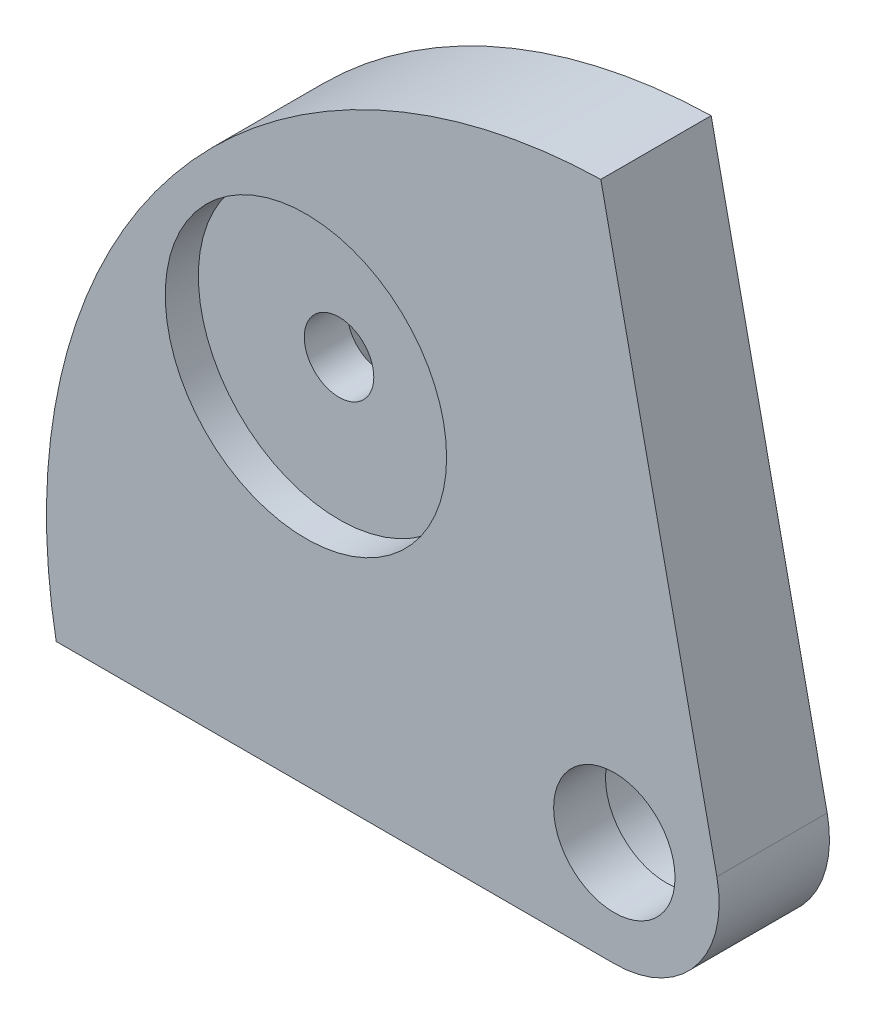
SolidWorks part; units mm, degrees
material "2024 Alloy"
ref_plane "Front Plane" through (0, 0, 0) normal (0, 0, 1) x (1, 0, 0)
ref_plane "Top Plane" through (0, 0, 0) normal (0, 1, 0) x (1, 0, 0)
ref_plane "Right Plane" through (0, 0, 0) normal (1, 0, 0) x (0, 0, -1)
sketch "Sketch4" plane through (0, 0, 0) normal (0, 0, 1) x (1, 0, 0)
  line L0 (0, 0) -> (9.2924, 1.9752) construction
  line L4 (0, 0) -> (-39.9969, 32.3889) construction
  line L5 (0, 0) -> (7.3829, -5.9785) construction
  line L6 (0, 0) -> (0, -9.5) construction
  line L14 (9.2924, 1.9752) -> (-1.2242, 51.4519)
  line L15 (0, -9.5) -> (-50.5821, -9.5)
  circle A2 centre (0, 0) radius 5.5
  circle A6 centre (-27.9512, 22.6344) radius 3
  arc A7 (0, -9.5) -> (9.2924, 1.9752) centre (0, 0) ccw
  arc A8 (-1.2242, 51.4519) -> (-50.5821, -9.5) centre (0, 0) ccw
  point P2 (-27.9512, 22.6344)
  dimension "D1" = 15.5
  dimension "D2" = 35.9665
  dimension "D3" = 9.5
  dimension "D4" = 129
  dimension "D5" = 11
  dimension "D6" = 129
  dimension "D7" = 39
  dimension "D8" = 39
other "AlignGroup1"
extrude "Boss-Extrude2" add sketch "Sketch4" along normal blind 10
hole_wizard "CSK for M6 Hex Socket Countersunk Cap Screw1" positions "Sketch5" profile "Sketch6" countersink size "M6" standard "ISO" end condition through all
sketch "Sketch5" plane through (0, 0, 0) normal (0, 0, -1) x (-1, 0, 0)
  point P0 (27.9512, 22.6344)
sketch "Sketch6" plane through (-27.9512, 22.6344, 0) normal (1, 0, 0) x (0, 1, 0)
  line L0 (0, 0) -> (0, 10)
  line L1 (0, 10) -> (3.15, 10)
  line L2 (3.15, 10) -> (3.15, 3.1)
  line L3 (3.15, 3.1) -> (6.25, 0)
  line L5 (6.25, 0) -> (0, 0)
  line L6 (-3.15, 3.1) -> (-6.25, 0) construction
  line L11 (0, -6.35) -> (0, 107.95) construction
  dimension "Thru Hole Dia." = 6.3
  dimension "Thru Hole Depth" = 10
  dimension "Near C'Sink Dia." = 12.5
  dimension "Near C'Sink Angle" = 90
sketch "Sketch7" plane through (0, 0, 0) normal (0, 0, -1) x (-1, 0, 0)
  circle A0 centre (0, 0) radius 6.65
extrude "Cut-Extrude1" cut sketch "Sketch7" against normal blind 5.3
sketch "Sketch8" plane through (0, 0, 10) normal (0, 0, 1) x (1, 0, 0)
  circle A0 centre (-27.9512, 22.6344) radius 12.75
extrude "Cut-Extrude2" cut sketch "Sketch8" against normal blind 3
